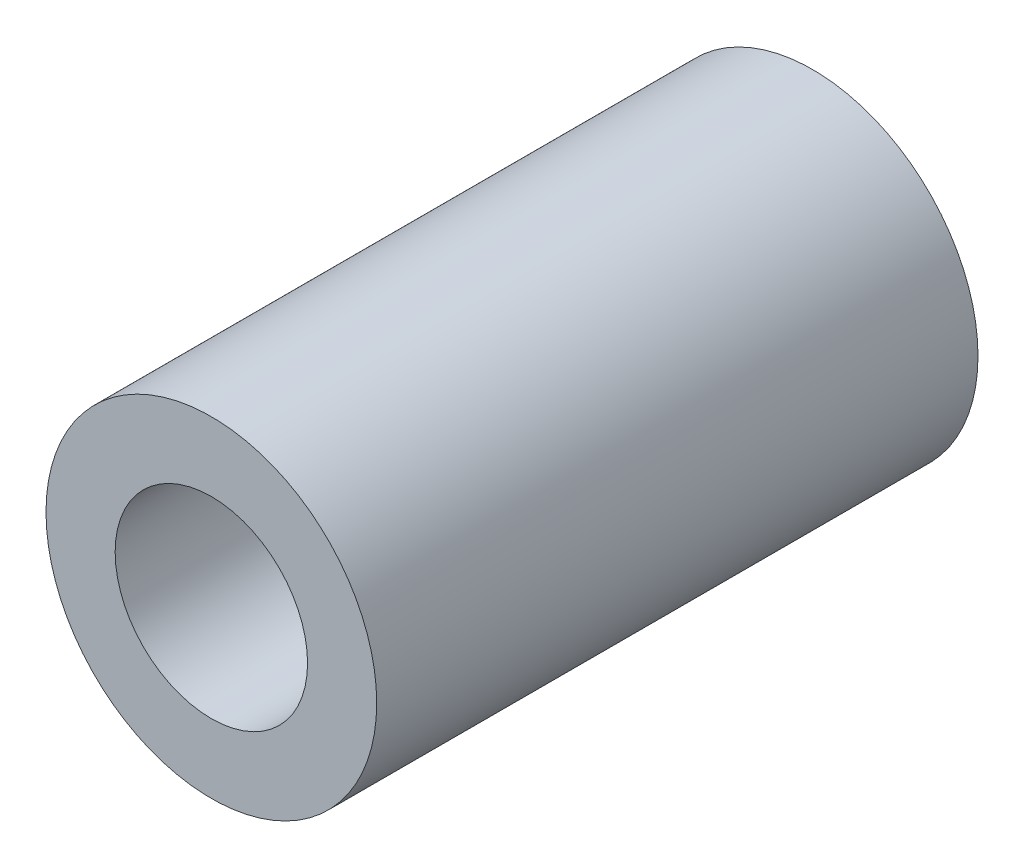
SolidWorks part; units mm, degrees
ref_plane "Front Plane" through (0, 0, 0) normal (0, 0, 1) x (1, 0, 0)
ref_plane "Top Plane" through (0, 0, 0) normal (0, 1, 0) x (1, 0, 0)
ref_plane "Right Plane" through (0, 0, 0) normal (1, 0, 0) x (0, 0, -1)
sketch "草圖1" plane through (0, 0, 0) normal (0, 0, 1) x (1, 0, 0)
  circle A0 centre (0, 0) radius 2.75
  circle A1 centre (0, 0) radius 1.6
extrude "填料-伸長1" add sketch "草圖1" along normal blind 10
